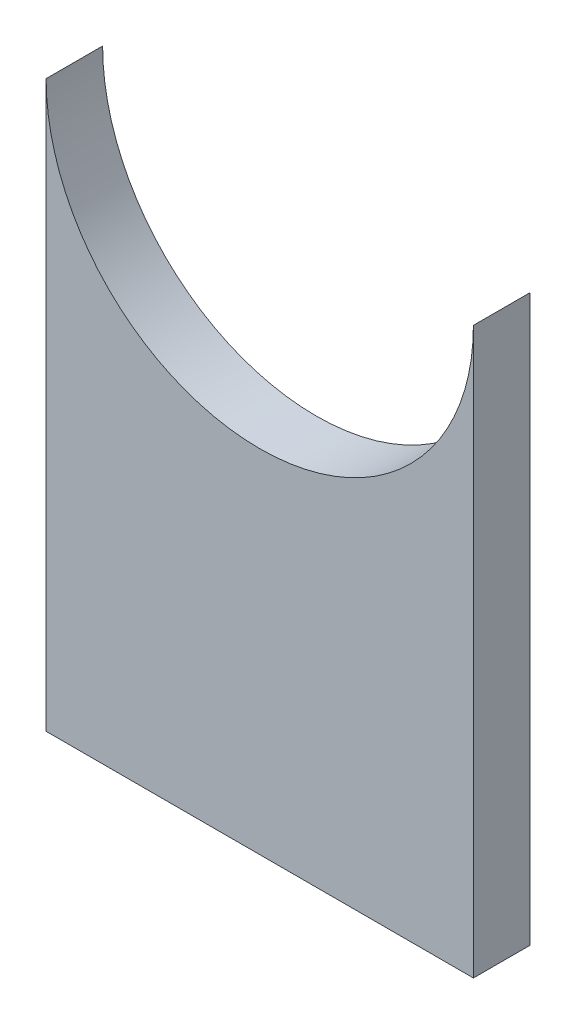
SolidWorks part; units mm, degrees
ref_plane "Front Plane" through (0, 0, 0) normal (0, 0, 1) x (1, 0, 0)
ref_plane "Top Plane" through (0, 0, 0) normal (0, 1, 0) x (1, 0, 0)
ref_plane "Right Plane" through (0, 0, 0) normal (1, 0, 0) x (0, 0, -1)
sketch "Sketch1" plane through (0, 0, 0) normal (0, 0, 1) x (1, 0, 0)
  line L0 (0, -63.5) -> (0, 36.9747) construction
  line L1 (-24.003, -63.5) -> (24.003, -63.5)
  line L2 (-24.003, -63.5) -> (-24.003, 0)
  line L4 (24.003, -63.5) -> (24.003, 0)
  line L5 (-24.003, -63.5) -> (24.003, 0) construction
  line L6 (-24.003, 0) -> (24.003, -63.5) construction
  line L7 (1.27, -50.8) -> (27.5942, -50.8) construction
  arc A0 (-24.003, 0) -> (24.003, 0) centre (0, 0) ccw
  point P3 (0, -31.75)
  dimension "D1" = 63.5
  dimension "D3" = 24.003
  dimension "D2" = 12.7
extrude "Boss-Extrude1" add sketch "Sketch1" along normal blind 6.35
